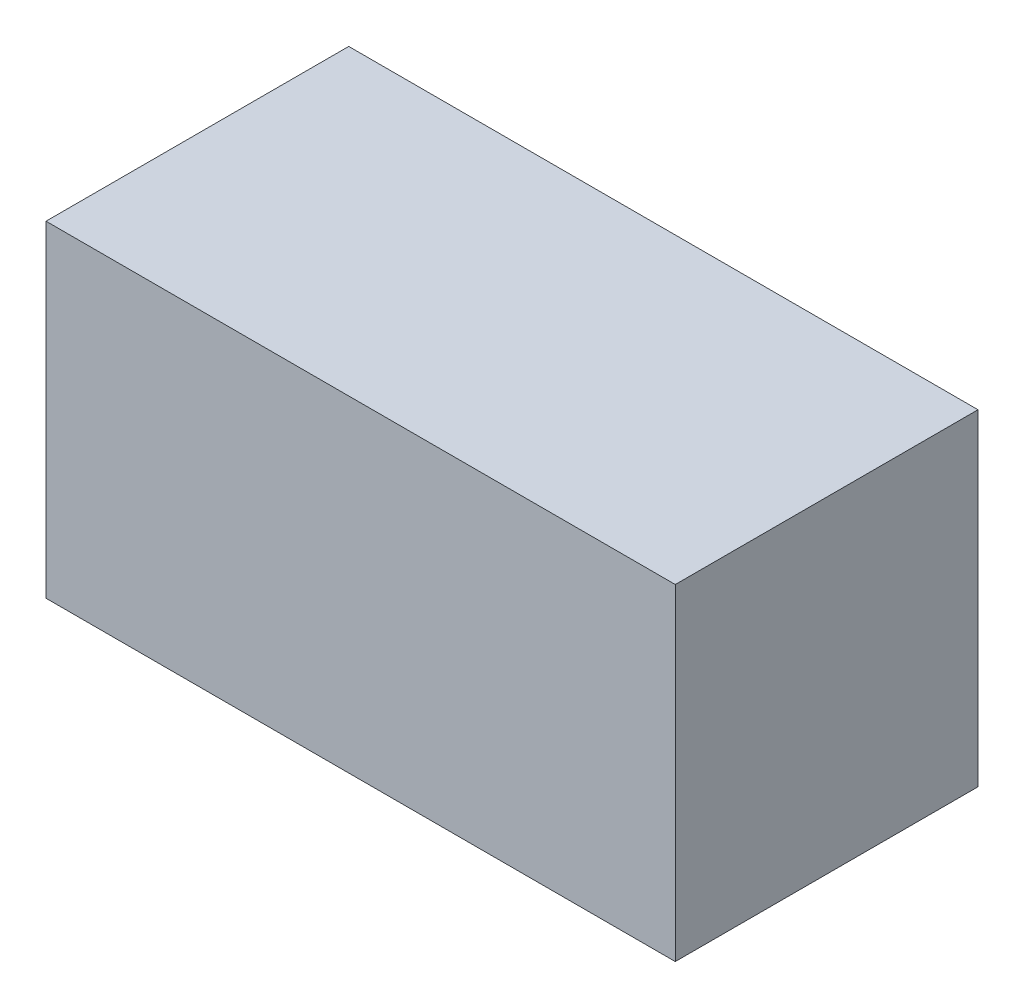
SolidWorks part; units mm, degrees
ref_plane "Front Plane" through (0, 0, 0) normal (0, 0, 1) x (1, 0, 0)
ref_plane "Top Plane" through (0, 0, 0) normal (0, 1, 0) x (1, 0, 0)
ref_plane "Right Plane" through (0, 0, 0) normal (1, 0, 0) x (0, 0, -1)
sketch "Sketch1" plane through (0, 0, 0) normal (0, 0, 1) x (1, 0, 0)
  line L0 (-1.37, -1.37) -> (3.91, -1.37)
  line L1 (3.91, -1.37) -> (3.91, 1.37)
  line L2 (3.91, 1.37) -> (-1.37, 1.37)
  line L3 (-1.37, 1.37) -> (-1.37, -1.37)
extrude "Component_Outline" add sketch "Sketch1" along normal blind 2.54 separate body
sketch3d "3DSketch1"
  line L0 (0, 0, 0) -> (1, 0, 0)
  line L1 (0, 0, 0) -> (0, 1, 0)
  line L2 (0, 0, 0) -> (0, 0, 1)
  point P0 (0, 0, 0)
